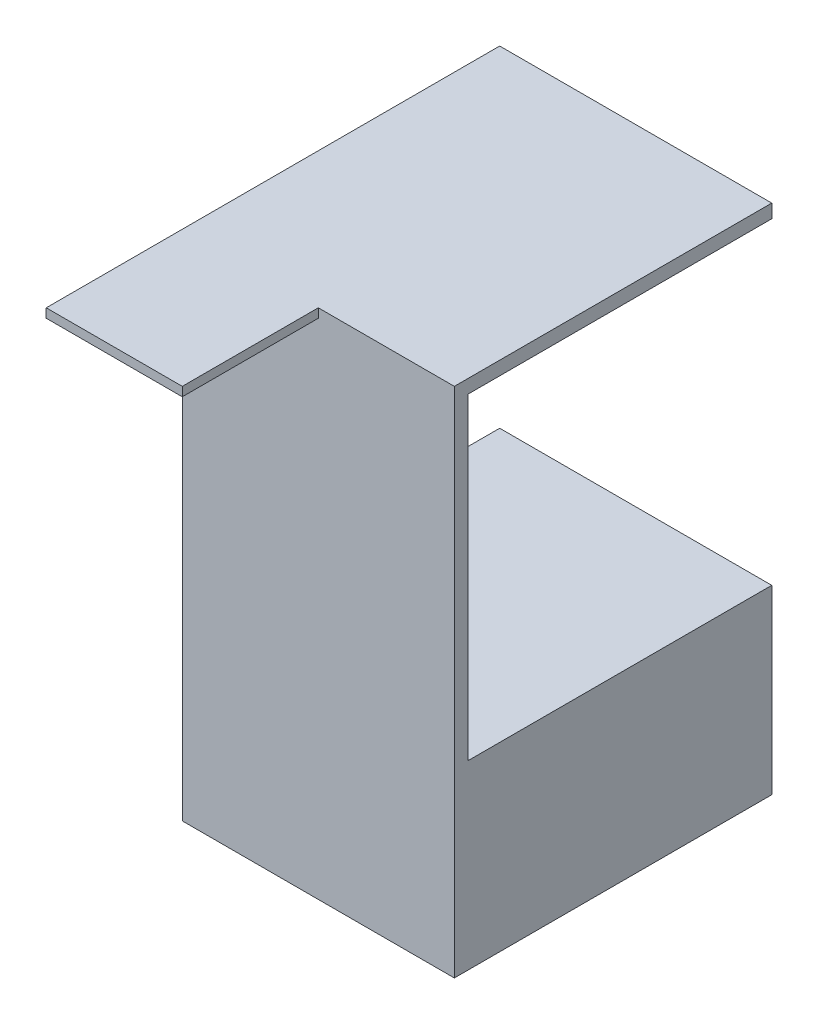
SolidWorks part; units mm, degrees
material "Oak"
ref_plane "Front Plane" through (0, 0, 0) normal (1, 0, 0) x (0, 1, 0)
ref_plane "Top Plane" through (0, 0, 0) normal (0, 0, 1) x (0, 1, 0)
ref_plane "Right Plane" through (0, 0, 0) normal (0, 1, 0) x (-1, 0, 0)
sketch "Sketch1" plane through (0, 0, 0) normal (0, 0, 1) x (0, 1, 0)
  line L1 (-350, 300) -> (350, 300)
  line L2 (-350, 300) -> (-350, -300)
  line L3 (-350, -300) -> (350, -300)
  line L4 (350, 300) -> (350, -300)
  line L5 (-350, 300) -> (350, -300) construction
  line L6 (-350, -300) -> (350, 300) construction
  point P0 (0, 0)
  dimension "D1" = 700
  dimension "D2" = 600
extrude "Boss-Extrude1" add sketch "Sketch1" along normal blind 30
sketch "Sketch2" plane through (0, 350, 0) normal (0, 1, 0) x (-1, 0, 0)
  line L0 (300, 30) -> (300, 0) construction
  line L1 (-300, 30) -> (300, 30)
  line L2 (-300, 30) -> (-300, -670)
  line L3 (-300, -670) -> (300, -670)
  line L4 (300, 30) -> (300, -670)
  dimension "D1" = 700
extrude "Boss-Extrude2" add sketch "Sketch2" along normal blind 30
sketch "Sketch3" plane through (0, 0, 30) normal (0, 0, 1) x (1, 0, 0)
  line L0 (300, -350) -> (300, 380) construction
  line L1 (-300, -350) -> (300, -350)
  line L2 (-300, -350) -> (-300, -750)
  line L3 (-300, -750) -> (300, -750)
  line L4 (300, -350) -> (300, -750)
  dimension "D1" = 400
extrude "Boss-Extrude3" add sketch "Sketch3" against normal blind 700
sketch "Sketch4" plane through (0, 0, 30) normal (0, 0, 1) x (1, 0, 0)
  line L0 (300, -750) -> (300, 380) construction
  line L1 (-300, 380) -> (0, 380)
  line L2 (-300, 380) -> (-300, 360)
  line L3 (-300, 360) -> (0, 360)
  line L4 (0, 380) -> (0, 360)
  dimension "D1" = 20
  dimension "D2" = 300
extrude "Boss-Extrude4" add sketch "Sketch4" along normal blind 300
